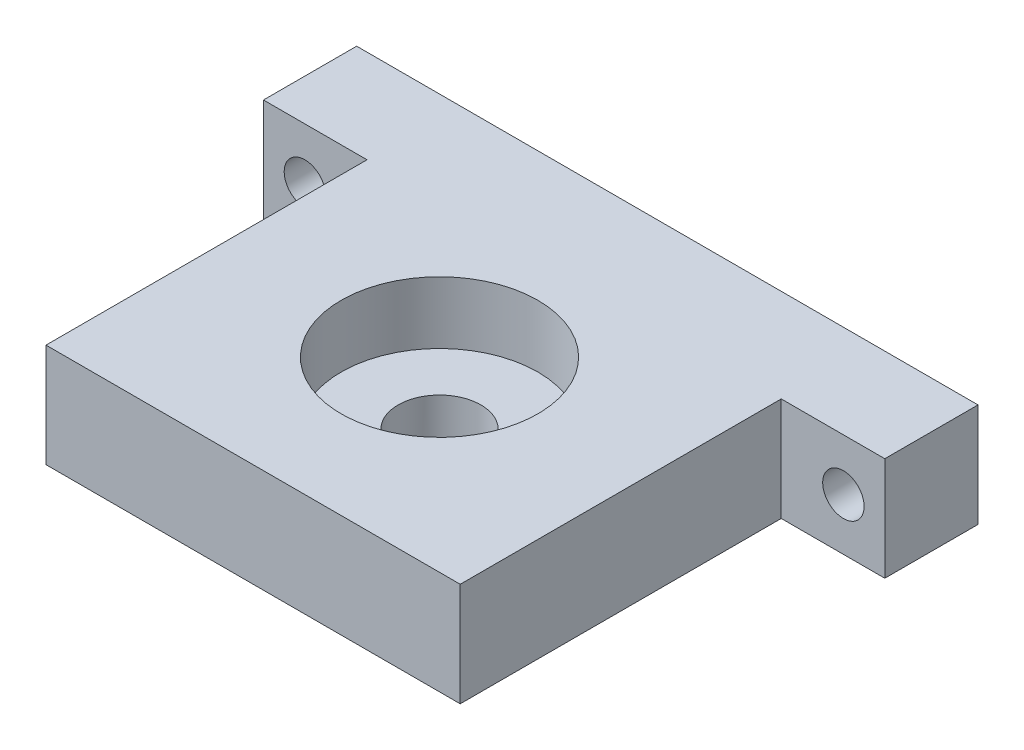
SolidWorks part; units mm, degrees
ref_plane "Front Plane" through (0, 0, 0) normal (0, 0, 1) x (1, 0, 0)
ref_plane "Top Plane" through (0, 0, 0) normal (0, 1, 0) x (1, 0, 0)
ref_plane "Right Plane" through (0, 0, 0) normal (1, 0, 0) x (0, 0, -1)
sketch "Sketch1" plane through (0, 0, 0) normal (0, 1, 0) x (1, 0, 0)
  line L1 (-20, -20) -> (20, -20)
  line L2 (-20, -20) -> (-20, 11)
  line L3 (-20, 20) -> (20, 20)
  line L4 (20, -20) -> (20, 11)
  line L5 (-20, -20) -> (20, 20) construction
  line L6 (-20, 20) -> (20, -20) construction
  line L7 (-20, 20) -> (-30, 20)
  line L9 (-20, 11) -> (-30, 11)
  line L10 (-30, 20) -> (-30, 11)
  line L11 (20, 20) -> (30, 20)
  line L13 (20, 11) -> (30, 11)
  line L14 (30, 20) -> (30, 11)
  point P0 (0, 0)
  dimension "D1" = 40
  dimension "D2" = 40
  dimension "D3" = 9
  dimension "D4" = 10
  dimension "D5" = 10
  dimension "D6" = 9
extrude "Boss-Extrude1" add sketch "Sketch1" along normal blind 10
ref_plane "Plane1" through (-30, 10, -20) normal (-1, 0, 0) x (0, 0, 1)
sketch "Sketch3" plane through (0, 10, 0) normal (0, 1, 0) x (1, 0, 0)
  line L0 (-20, -20) -> (20, -20) construction
  circle A0 centre (0, -2) radius 9.5
  dimension "D1" = 19
  dimension "D2" = 18
extrude "Cut-Extrude1" cut sketch "Sketch3" against normal blind 6 and the other way through all
sketch "Sketch4" plane through (0, 4, 0) normal (0, 1, 0) x (1, 0, 0)
  circle A0 centre (0, -2) radius 4
  dimension "D1" = 8
extrude "Cut-Extrude2" cut sketch "Sketch4" against normal blind 10
sketch "Sketch5" plane through (0, 0, -20) normal (0, 0, -1) x (-1, 0, 0)
  line L0 (-30, 10) -> (-30, 0) construction
  line L1 (-30, 0) -> (30, 0) construction
  line L3 (30, 10) -> (30, 0) construction
  circle A0 centre (-26, 5) radius 2
  circle A1 centre (26, 5) radius 2
  point P10 (0, 0)
  dimension "D1" = 4
  dimension "D2" = 4
  dimension "D3" = 4
  dimension "D4" = 5
  dimension "D5" = 5
  dimension "D6" = 4
extrude "Cut-Extrude3" cut sketch "Sketch5" against normal through all both and the other way through all
